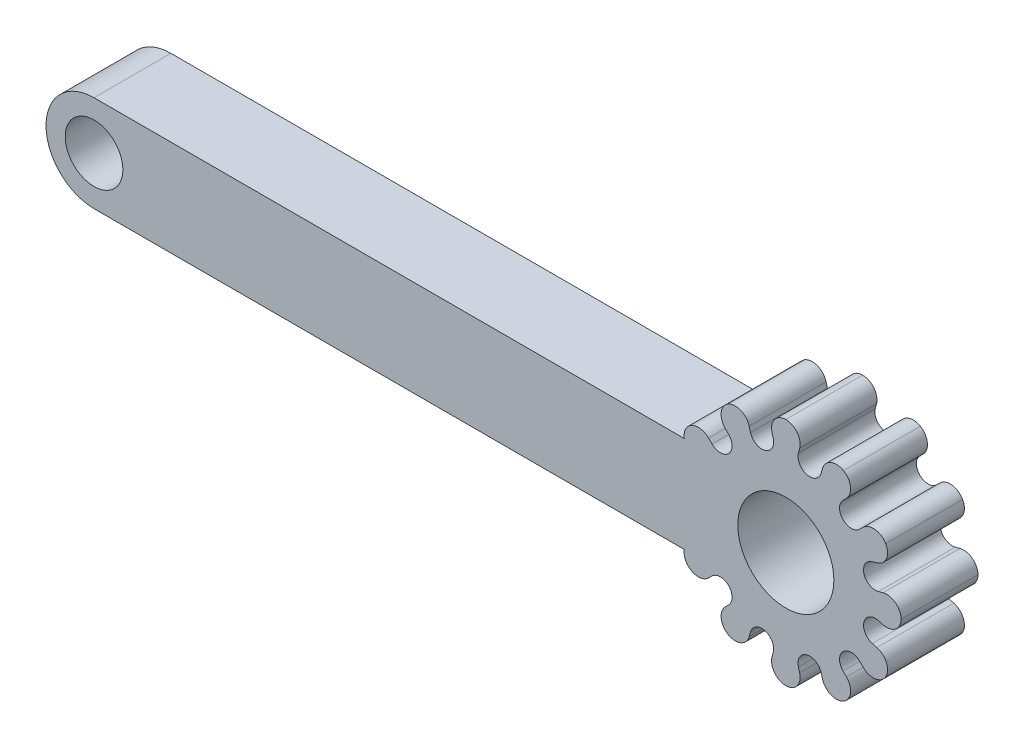
SolidWorks part; units mm, degrees
ref_plane "Front Plane" through (0, 0, 0) normal (0, 0, 1) x (1, 0, 0)
ref_plane "Top Plane" through (0, 0, 0) normal (0, 1, 0) x (1, 0, 0)
ref_plane "Right Plane" through (0, 0, 0) normal (1, 0, 0) x (0, 0, -1)
sketch "Sketch1" plane through (0, 0, 0) normal (0, 0, 1) x (1, 0, 0)
  line L0 (18, 0) -> (-18, 0) construction
  line L1 (-18, 2.5) -> (12.5456, 2.5)
  line L2 (-18, -2.5) -> (12.5456, -2.5)
  arc A0 (-18, 2.5) -> (-18, -2.5) centre (-18, 0) ccw
  circle A1 centre (-18, 0) radius 1.5
  arc A2 (12.5456, -2.5) -> (12.5456, 2.5) centre (18, 0) ccw
  point P4 (0, 0)
  dimension "D2" = 12
  dimension "D3" = 3
  dimension "D4" = 5
  dimension "D1" = 36
extrude "Boss-Extrude1" add sketch "Sketch1" along normal blind 4
sketch "Sketch2" plane through (0, 0, 4) normal (0, 0, 1) x (1, 0, 0)
  line L0 (18, 6) -> (18, -6) construction
  line L1 (18, 0) -> (21, 5.1962) construction
  line L2 (18, 0) -> (19.2475, 4.6558) construction
  line L3 (18.72, 5.06) -> (18.6545, 4.81)
  line L4 (18.6545, 4.81) -> (19.8405, 4.5015) construction
  line L5 (19.9065, 4.7421) -> (19.8405, 4.5015)
  arc A0 (12.5456, -2.5) -> (12.5456, 2.5) centre (18, 0) ccw construction
  arc A1 (18, 6) -> (18.72, 5.06) centre (17.9945, 5.25) cw
  arc A2 (18.6545, 4.81) -> (19.8405, 4.5015) centre (19.2475, 4.6558) ccw
  arc A3 (21, 5.1962) -> (19.9065, 4.7421) centre (20.6298, 4.5439) ccw
  arc A6 (18, 6) -> (21, 5.1962) centre (18.963, 3.5938) cw
  dimension "D4" = 0.94
  dimension "D6" = 0.75
  dimension "D1" = 30
  dimension "D2" = 4.82
  dimension "D3" = 15
  dimension "D5" = 0.72
  dimension "D8" = 0.25
extrude "Cut-Extrude1" cut sketch "Sketch2" against normal through all
pattern_circular "CirPattern1" count 12 over 360 about axis through (18, 0, 0) along (0, 0, 1) of "Cut-Extrude1"
sketch "Sketch3" plane through (0, 0, 4) normal (0, 0, 1) x (1, 0, 0)
  line L0 (12.3194, 2.5) -> (-18, 2.5) construction
  line L1 (10.2871, 2.5) -> (16.2777, 2.5)
  line L2 (10.2871, 2.5) -> (10.2871, -2.5)
  line L3 (10.2871, -2.5) -> (16.2777, -2.5)
  line L4 (16.2777, 2.5) -> (16.2777, -2.5)
  line L5 (-18, -2.5) -> (12.3194, -2.5) construction
extrude "Boss-Extrude2" add sketch "Sketch3" against normal blind 4
sketch "Sketch4" plane through (0, 0, 4) normal (0, 0, 1) x (1, 0, 0)
  line L0 (18, 6) -> (18, -6) construction
  circle A0 centre (18, 0) radius 2.5
  point P6 (0, 0)
  point P7 (18, 0)
  dimension "D1" = 5
extrude "Cut-Extrude2" cut sketch "Sketch4" against normal through all
